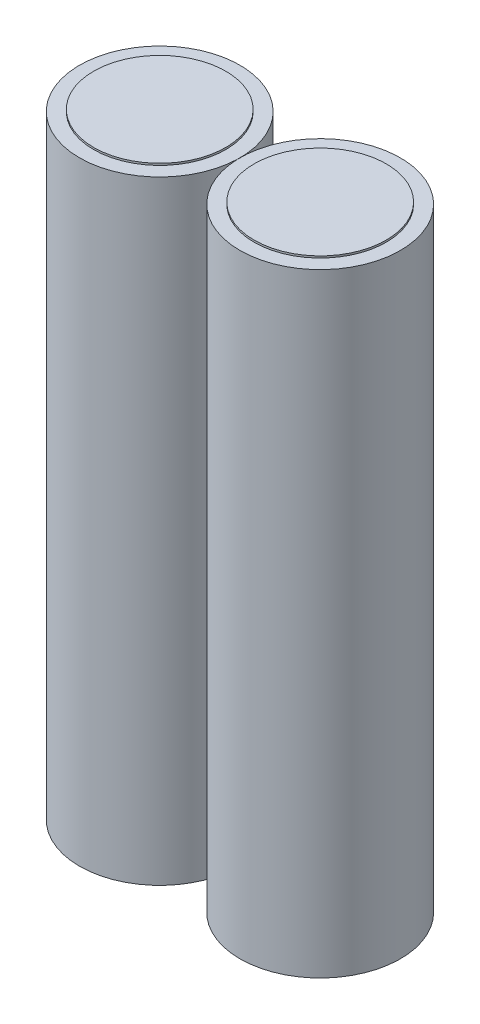
SolidWorks part; units mm, degrees
ref_plane "Front Plane" through (0, 0, 0) normal (0, 0, 1) x (1, 0, 0)
ref_plane "Top Plane" through (0, 0, 0) normal (0, 1, 0) x (1, 0, 0)
ref_plane "Right Plane" through (0, 0, 0) normal (1, 0, 0) x (0, 0, -1)
sketch "Sketch1" plane through (0, 0, 0) normal (0, 1, 0) x (1, 0, 0)
  line L0 (0, 0) -> (17, 0) construction
  circle A0 centre (0, 0) radius 8.5
  circle A1 centre (17, 0) radius 8.5
  dimension "D1" = 17
extrude "Boss-Extrude1" add sketch "Sketch1" along normal blind 65
sketch "Sketch2" plane through (0, 0, 0) normal (0, -1, 0) x (1, 0, 0)
  circle A0 centre (17, 0) radius 5
  circle A1 centre (0, 0) radius 5
  dimension "D1" = 10
extrude "Boss-Extrude2" add sketch "Sketch2" along normal blind 1
sketch "Sketch3" plane through (0, 65, 0) normal (0, 1, 0) x (1, 0, 0)
  circle A0 centre (17, 0) radius 7
  circle A1 centre (0, 0) radius 7
  dimension "D1" = 14
extrude "Boss-Extrude3" add sketch "Sketch3" along normal blind 0.2
